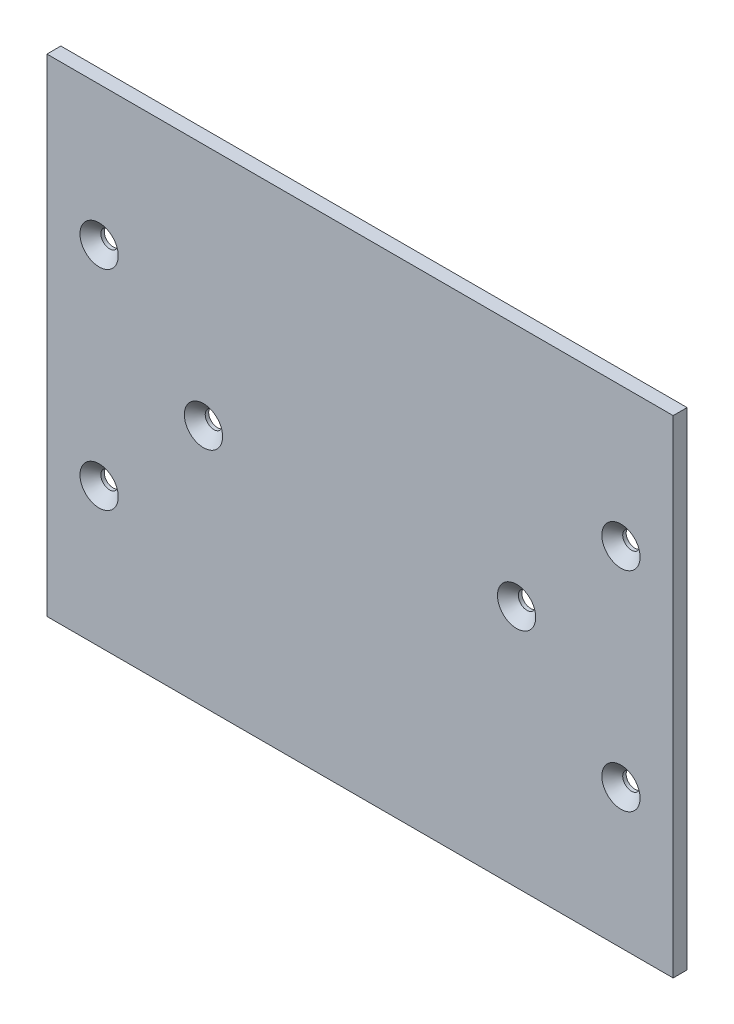
SolidWorks part; units mm, degrees
ref_plane "Front" through (0, 0, 0) normal (0, 0, 1) x (1, 0, 0)
ref_plane "Top" through (0, 0, 0) normal (0, 1, 0) x (1, 0, 0)
ref_plane "Right" through (0, 0, 0) normal (1, 0, 0) x (0, 0, -1)
sketch "Sketch1" plane through (0, 0, 0) normal (0, 0, 1) x (1, 0, 0)
  line L0 (0, 70) -> (0, 0) construction
  line L1 (-90, 70) -> (90, 70)
  line L2 (-90, 70) -> (-90, -70)
  line L3 (-90, -70) -> (90, -70)
  line L4 (90, 70) -> (90, -70)
  line L5 (0, 0) -> (0, -70) construction
  point P9 (0, 70)
  dimension "D1" = 180
  dimension "D2" = 140
extrude "Boss-Extrude1" add sketch "Sketch1" along normal blind 4
sketch "Sketch2" plane through (0, 0, 0) normal (0, 0, -1) x (-1, 0, 0)
  line L0 (75, 30) -> (75, -30) construction
  line L1 (75, -30) -> (90, -30) construction
  line L2 (90, 70) -> (90, -70) construction
  line L3 (-75, -30) -> (-75, 30) construction
  line L4 (-75, 30) -> (-90, 30) construction
  line L5 (-90, -70) -> (-90, 70) construction
  line L6 (-75, 0) -> (-45, 0) construction
  line L7 (75, 0) -> (45, 0) construction
  circle A0 centre (-75, 30) radius 2.5
  circle A1 centre (-75, -30) radius 2.5
  circle A2 centre (75, -30) radius 2.5
  circle A3 centre (75, 30) radius 2.5
  circle A4 centre (45, 0) radius 2.5
  circle A5 centre (-45, 0) radius 2.5
  point P8 (-75, 0)
  point P15 (-90, 0)
  point P16 (75, 0)
  dimension "D3" = 5
  dimension "D1" = 15
  dimension "D2" = 60
  dimension "D4" = 30
extrude "Cut-Extrude1" cut sketch "Sketch2" against normal up to next
chamfer "Chamfer1" distance 3 angle 45 6 edges at (-72.5, 30, 4) (-72.5, -30, 4) (77.5, -30, 4) (77.5, 30, 4) (-42.5, 0, 4) (47.5, 0, 4)
